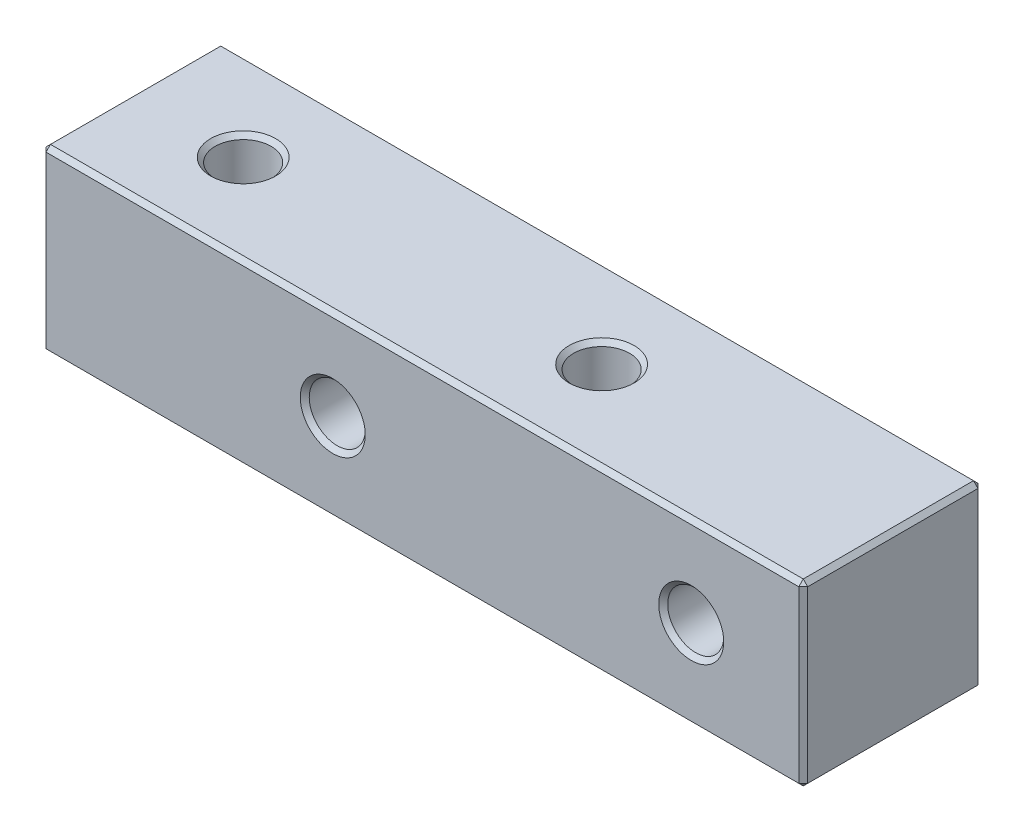
SolidWorks part; units mm, degrees
ref_plane "前视基准面" through (0, 0, 0) normal (0, 0, 1) x (1, 0, 0)
ref_plane "上视基准面" through (0, 0, 0) normal (0, 1, 0) x (1, 0, 0)
ref_plane "右视基准面" through (0, 0, 0) normal (1, 0, 0) x (0, 0, -1)
sketch "草图1" plane through (0, 0, 0) normal (0, 1, 0) x (1, 0, 0)
  line L1 (-17, 4) -> (17, 4)
  line L2 (-17, 4) -> (-17, -4)
  line L3 (-17, -4) -> (17, -4)
  line L4 (17, 4) -> (17, -4)
  line L5 (-17, 4) -> (17, -4) construction
  line L6 (-17, -4) -> (17, 4) construction
  point P0 (0, 0)
  dimension "D1" = 8
  dimension "D2" = 34
extrude "凸台-拉伸1" add sketch "草图1" along normal mid plane 8
hole_wizard "M3 螺纹孔1" positions "草图4" profile "草图6" tap size "M3" standard "GB" end condition through all
sketch "草图4" plane through (0, 4, 0) normal (0, 1, 0) x (1, 0, 0)
  line L0 (-17, 4) -> (-17, -4) construction
  line L1 (0, 0) -> (-50000, 0) construction
  point P0 (-12, 0)
  point P2 (4, 0)
  dimension "D1" = 5
  dimension "D2" = 16
sketch "草图6" plane through (-12, 4, 0) normal (1, 0, 0) x (0, 0, 1)
  line L0 (0, 0) -> (0, 8)
  line L1 (0, 8) -> (1.25, 8)
  line L2 (1.25, 8) -> (1.25, 0)
  line L5 (1.25, 0) -> (0, 0)
  line L11 (0, -6.35) -> (0, 107.95) construction
  dimension "通孔螺纹孔钻头直径" = 2.5
  dimension "通孔螺纹孔钻头深度" = 8
cosmetic thread "孔螺蚊线1" parameters "D2"=3
cosmetic thread "孔螺蚊线2" parameters "D2"=3
hole_wizard "M3 螺纹孔2" positions "草图7" profile "草图8" tap size "M3" standard "GB" end condition through all
sketch "草图7" plane through (0, 0, -4) normal (0, 0, -1) x (-1, 0, 0)
  line L0 (0, 0) -> (-50000, 0) construction
  line L1 (-17, 4) -> (-17, -4) construction
  point P0 (-12, 0)
  point P2 (4, 0)
  dimension "D1" = 5
  dimension "D2" = 16
sketch "草图8" plane through (12, 0, -4) normal (1, 0, 0) x (0, 1, 0)
  line L0 (0, 0) -> (0, 8)
  line L1 (0, 8) -> (1.25, 8)
  line L2 (1.25, 8) -> (1.25, 0)
  line L5 (1.25, 0) -> (0, 0)
  line L11 (0, -6.35) -> (0, 107.95) construction
  dimension "通孔螺纹孔钻头直径" = 2.5
  dimension "通孔螺纹孔钻头深度" = 8
cosmetic thread "孔螺蚊线3"
cosmetic thread "孔螺蚊线4"
chamfer "倒角1" distance 0.2 angle 45 20 edges at (4, -4, 1.25) (-12, -4, 1.25) (-5.25, 0, 4) (10.75, 0, 4) (4, 4, 1.25) (-12, 4, 1.25) (-17, -4, 0) (17, -4, 0) (-17, 0, 4) (0, -4, 4) (17, 0, 4) (0, 4, 4) (-17, 4, 0) (17, 4, 0) (17, 0, -4) (0, 4, -4) (-17, 0, -4) (0, -4, -4) (-5.25, 0, -4) (10.75, 0, -4)
